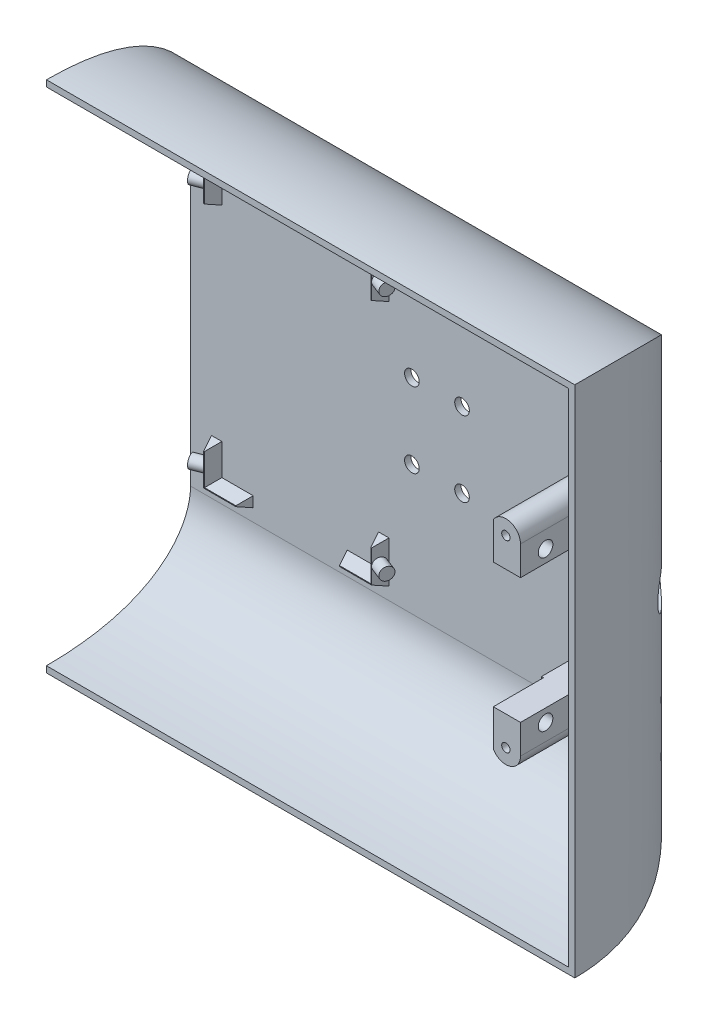
SolidWorks part; units mm, degrees
ref_plane "Plan de face" through (0, 0, 0) normal (0, 0, 1) x (1, 0, 0)
ref_plane "Plan de dessus" through (0, 0, 0) normal (0, 1, 0) x (1, 0, 0)
ref_plane "Plan de droite" through (0, 0, 0) normal (1, 0, 0) x (0, 0, -1)
sketch "Esquisse1" plane through (0, 0, 0) normal (0, 0, 1) x (1, 0, 0)
  line L1 (100.6491, 73.8649) -> (-4.3509, 73.8649)
  line L2 (100.6491, 73.8649) -> (100.6491, -6.1351)
  line L3 (100.6491, -6.1351) -> (-4.3509, -6.1351)
  line L4 (-4.3509, 73.8649) -> (-4.3509, 33.8649)
  line L7 (-4.3509, 33.8649) -> (-4.3509, -6.1351)
  dimension "D1" = 105
  dimension "D2" = 80
extrude "Boss.-Extru.1" add sketch "Esquisse1" along normal blind 1.5
ref_plane "Plan2" through (-4.3509, 0, 0) normal (1, 0, 0) x (0, 0, -1)
sketch "Esquisse3" plane through (0, 0, 1.5) normal (0, 0, 1) x (1, 0, 0)
  line L0 (100.6491, 33.8649) -> (-4.3509, 33.8649) construction
  line L1 (100.6491, -6.1351) -> (100.6491, 73.8649) construction
  line L2 (60.6491, 66.3622) -> (60.6491, 22.1054) construction
  line L3 (48.6491, 66.3622) -> (48.6491, 22.1054) construction
  line L4 (-4.3509, 73.8649) -> (-4.3509, -6.1351) construction
  circle A1 centre (48.6491, 42.8649) radius 1.75
  circle A2 centre (48.6491, 24.8649) radius 1.75
  circle A3 centre (60.6491, 24.8649) radius 1.75
  circle A4 centre (60.6491, 42.8649) radius 1.75
  dimension "D1" = 3.5
  dimension "D2" = 3.5
  dimension "D3" = 3.5
  dimension "D4" = 3.5
  dimension "D7" = 9
  dimension "D8" = 9
  dimension "D9" = 9
  dimension "D5" = 12
  dimension "D6" = 9
  dimension "D10" = 40
extrude "Enlèv. mat.-Extru.1" cut sketch "Esquisse3" against normal up to next
sketch "Esquisse19" plane through (0, 0, 0) normal (0, 0, -1) x (-1, 0, 0)
  line L0 (4.3509, -6.1351) -> (-100.6491, -6.1351)
  line L1 (-100.6491, -6.1351) -> (-100.6491, 73.8649)
  line L2 (-100.6491, 73.8649) -> (4.3509, 73.8649)
sketch "Esquisse4" plane through (0, 0, 1.5) normal (0, 0, -1) x (-1, 0, 0)
  line L0 (-100.6491, 33.8649) -> (-3.0389, 33.8649) construction
  line L1 (-3.1491, -0.6351) -> (-40.6491, -0.6351) construction
  line L2 (-3.1491, -0.6351) -> (-3.1491, 65.8649) construction
  line L3 (-5.6491, 68.3649) -> (-38.1491, 68.3649) construction
  line L4 (-3.1491, 65.8649) -> (-3.1491, 55.8649)
  line L5 (-100.6491, -6.1351) -> (-100.6491, 73.8649) construction
  line L6 (-3.1491, 55.8649) -> (-0.6491, 55.8649)
  line L7 (-0.6491, -3.1351) -> (-43.1491, -3.1351) construction
  line L8 (-0.6491, -3.1351) -> (-0.6491, 65.8649) construction
  line L9 (-5.6491, 70.8649) -> (-38.1491, 70.8649) construction
  line L10 (-43.1491, -3.1351) -> (-43.1491, 65.8649) construction
  line L11 (-40.6491, -0.6351) -> (-40.6491, 65.8649) construction
  line L12 (-0.6491, 55.8649) -> (-0.6491, 65.8649)
  line L13 (-0.6491, 65.8649) -> (-3.1491, 65.8649)
  line L14 (-5.6491, 70.8649) -> (-5.6491, 68.3649)
  line L15 (-40.6491, 65.8649) -> (-40.6491, 55.8649)
  line L16 (-40.6491, 55.8649) -> (-43.1491, 55.8649)
  line L17 (-43.1491, 65.8649) -> (-40.6491, 65.8649)
  line L18 (-38.1491, 70.8649) -> (-38.1491, 68.3649)
  line L19 (-43.1491, 55.8649) -> (-43.1491, 65.8649)
  line L20 (-40.6491, 6.8649) -> (-43.1491, 6.8649)
  line L21 (-43.1491, 6.8649) -> (-43.1491, -3.1351)
  line L22 (-43.1491, -3.1351) -> (-33.1491, -3.1351)
  line L23 (-33.1491, -3.1351) -> (-33.1491, -0.6351)
  line L24 (-33.1491, -0.6351) -> (-40.6491, -0.6351)
  line L25 (-10.6491, -0.6351) -> (-10.6491, -3.1351)
  line L26 (-10.6491, -3.1351) -> (-0.6491, -3.1351)
  line L27 (-0.6491, -3.1351) -> (-0.6491, 6.8649)
  line L28 (-0.6491, 6.8649) -> (-3.1491, 6.8649)
  line L29 (-3.1491, 6.8649) -> (-3.1491, -0.6351)
  line L30 (-3.1491, -0.6351) -> (-10.6491, -0.6351)
  line L31 (-5.6491, 70.8649) -> (-15.6491, 70.8649)
  line L32 (-15.6491, 70.8649) -> (-15.6491, 68.3649)
  line L33 (-15.6491, 68.3649) -> (-5.6491, 68.3649)
  line L34 (-38.1491, 70.8649) -> (-28.1491, 70.8649)
  line L35 (-28.1491, 70.8649) -> (-28.1491, 68.3649)
  line L36 (-28.1491, 68.3649) -> (-38.1491, 68.3649)
  line L37 (-40.6491, 6.8649) -> (-40.6491, -0.6351)
  circle A0 centre (-48.6491, 24.8649) radius 1.75 construction
  point P3 (-70.3996, 0.9688)
  point P4 (-51.6001, 33.8649)
  point P14 (-70.3501, 69.9688)
  dimension "D2" = 2.5
  dimension "D3" = 2.5
  dimension "D4" = 2.5
  dimension "D5" = 34.5
  dimension "D6" = 5.5
  dimension "D7" = 2.5
  dimension "D8" = 32.5
  dimension "D9" = 2.5
  dimension "D10" = 2.5
  dimension "D11" = 34.5
  dimension "D12" = 2.5
  dimension "D13" = 2.5
  dimension "D14" = 10
  dimension "D15" = 10
  dimension "D16" = 10
  dimension "D17" = 10
  dimension "D18" = 10
  dimension "D19" = 10
  dimension "D20" = 10
  dimension "D21" = 10
extrude "Boss.-Extru.2" add sketch "Esquisse4" against normal blind 3 draft 21
sketch "Esquisse7" plane through (-4.3509, 0, 0) normal (-1, 0, 0) x (0, 0, 1)
  line L6 (1.5, 73.8649) -> (0, 73.8649)
  line L7 (36, 95.3649) -> (36, 93.8649)
  line L8 (37.4577, 93.8649) -> (34.5423, 93.8649) construction
  line L10 (1.5, 73.8649) -> (1.5, -6.1351) construction
  line L11 (1.5, 81.9984) -> (1.5, 65.5079) construction
  line L12 (0, 73.8649) -> (0, -6.1351) construction
  line L13 (0, 79.8432) -> (0, 67.8865) construction
  line L14 (59.3831, 95.3649) -> (12.6169, 95.3649) construction
  spline S0 degree 3 poles (0, 73.8649) (0, 82.2935) (9.1969, 95.3649) (36, 95.3649) knots 0 0 0 0 1 1 1 1
  spline S1 degree 3 poles (1.5, 73.8649) (1.5, 82.116) (9.4276, 93.8649) (36, 93.8649) knots 0 0 0 0 1 1 1 1
  dimension "D2" = 36
  dimension "D1" = 20
sweep "Balayage1" add profiles "Esquisse7" path "Esquisse19"
sketch "Esquisse8" plane through (0, 0, 0) normal (0, 0, -1) x (-1, 0, 0)
  line L0 (-100.6491, 33.8649) -> (-183.7283, 33.8649) construction
  line L2 (-105.6491, 64.6793) -> (-105.6491, 3.4231) construction
  line L3 (-100.6491, 73.8649) -> (-100.6491, -6.1351) construction
  line L4 (-100.6491, -6.1351) -> (-100.6491, 73.8649) construction
  circle A0 centre (-105.6491, 55.8649) radius 1
  circle A1 centre (-105.6491, 11.8649) radius 1
  point P2 (-100.6491, 33.8649)
  dimension "D3" = 2
  dimension "D4" = 2
  dimension "D1" = 22
  dimension "D2" = 22
  dimension "D5" = 5
extrude "Enlèv. mat.-Extru.2" cut sketch "Esquisse8" against normal up to next
sketch "Esquisse9" plane through (0, 0, 36) normal (0, 0, 1) x (1, 0, 0)
  line L2 (102.1491, 55.8649) -> (102.1491, 48.8649)
  line L3 (102.1491, 48.8649) -> (109.1491, 48.8649)
  line L4 (109.1491, 55.8649) -> (109.1491, 48.8649)
  line L6 (109.1491, 11.8649) -> (109.1491, 18.8649)
  line L7 (109.1491, 18.8649) -> (102.1491, 18.8649)
  line L8 (102.1491, 11.8649) -> (102.1491, 18.8649)
  circle A0 centre (105.6491, 55.8649) radius 1
  circle A1 centre (105.6491, 11.8649) radius 1
  arc A2 (102.1491, 11.8649) -> (109.1491, 11.8649) centre (105.6491, 11.8649) ccw
  arc A3 (109.1491, 55.8649) -> (102.1491, 55.8649) centre (105.6491, 55.8649) ccw
  dimension "D1" = 2.5
  dimension "D2" = 2.5
  dimension "D3" = 2
  dimension "D4" = 2
  dimension "D5" = 30
extrude "Boss.-Extru.3" add sketch "Esquisse9" against normal up to next
sketch "Esquisse10" plane through (0, 0, 36) normal (0, 0, 1) x (1, 0, 0)
  line L0 (102.6491, 10.0621) -> (102.6491, 18.8649)
  line L2 (102.6491, 48.8649) -> (102.6491, 57.6676)
  line L3 (102.1491, 48.8649) -> (109.1491, 48.8649) construction
  line L4 (102.1491, 55.8649) -> (102.1491, 48.8649) construction
  line L5 (102.1491, 55.8649) -> (102.1491, 48.8649)
  line L6 (102.6491, 48.8649) -> (102.1491, 48.8649)
  line L7 (109.1491, 18.8649) -> (102.1491, 18.8649) construction
  line L8 (102.1491, 18.8649) -> (102.1491, 11.8649) construction
  line L9 (102.6491, 18.8649) -> (102.1491, 18.8649)
  line L10 (102.1491, 18.8649) -> (102.1491, 11.8649)
  line L11 (100.6491, 73.8649) -> (100.6491, -6.1351) construction
  circle A0 centre (105.6491, 55.8649) radius 3.5 construction
  circle A1 centre (105.6491, 11.8649) radius 3.5 construction
  arc A2 (109.1491, 55.8649) -> (102.1491, 55.8649) centre (105.6491, 55.8649) ccw construction
  arc A3 (102.1491, 11.8649) -> (109.1491, 11.8649) centre (105.6491, 11.8649) ccw construction
  arc A4 (102.6491, 57.6676) -> (102.1491, 55.8649) centre (105.6491, 55.8649) ccw
  arc A5 (102.1491, 11.8649) -> (102.6491, 10.0621) centre (105.6491, 11.8649) ccw
  dimension "D1" = 2
extrude "Enlèv. mat.-Extru.3" cut sketch "Esquisse10" against normal blind 12
sketch "Esquisse11" plane through (102.6491, 0, 0) normal (-1, 0, 0) x (0, 0, 1)
  line L0 (30, 48.8649) -> (30, 18.8649) construction
  line L4 (24, 48.8649) -> (36, 48.8649) construction
  line L5 (24, 18.8649) -> (36, 18.8649) construction
  line L6 (30, 48.8649) -> (30, 51.8649) construction
  line L7 (30, 15.8649) -> (30, 18.8649) construction
  circle A0 centre (30, 51.8649) radius 1.75
  circle A1 centre (30, 15.8649) radius 1.75
  point P6 (30, 48.8649)
  point P7 (30, 18.8649)
  dimension "D1" = 3.5
  dimension "D2" = 3.5
  dimension "D3" = 36
extrude "Enlèv. mat.-Extru.4" cut sketch "Esquisse11" against normal up to next
sketch "Esquisse16" plane through (102.1491, 0, 0) normal (-1, 0, 0) x (0, 0, 1)
  line L0 (1.5857, 48.8649) -> (1.5857, 55.8649) construction
  line L1 (1.5857, 39.8649) -> (16.5857, 39.8649)
  line L2 (1.5857, 39.8649) -> (1.5857, 27.8649)
  line L3 (1.5857, 27.8649) -> (16.5857, 27.8649)
  line L4 (16.5857, 39.8649) -> (16.5857, 27.8649)
  line L6 (1.5857, 48.8649) -> (24, 48.8649) construction
  line L7 (1.5857, 18.8649) -> (24, 18.8649) construction
  line L8 (16.5857, 39.8649) -> (16.5857, 48.8649) construction
  line L9 (16.5857, 27.8649) -> (16.5857, 18.8649) construction
  dimension "D1" = 15
  dimension "D2" = 12
extrude "Boss.-Extru.4" add sketch "Esquisse16" against normal up to next
sketch "Esquisse12" plane through (157.424, 0, -57.2977) normal (0.9397, 0, -0.342) x (-0.342, 0, -0.9397)
  circle A0 centre (-44.7183, 33.8649) radius 4.25
  dimension "D1" = 8.5
extrude "Enlèv. mat.-Extru.5" cut sketch "Esquisse12" against normal up to surface (73.5516 mm away)
sketch "Esquisse17" plane through (0, 0, 16.5857) normal (0, 0, 1) x (1, 0, 0)
  line L0 (117.8029, 39.8649) -> (102.1491, 39.8649) construction
  line L1 (107.1491, 39.8649) -> (111.1491, 39.8649)
  line L2 (107.1491, 39.8649) -> (107.1491, 27.8649)
  line L3 (107.1491, 27.8649) -> (111.1491, 27.8649)
  line L4 (111.1491, 39.8649) -> (111.1491, 27.8649)
  line L5 (117.8029, 27.8649) -> (102.1491, 27.8649) construction
  line L6 (102.1491, 27.8649) -> (102.1491, 39.8649) construction
  point P8 (102.1491, 33.8649)
  dimension "D1" = 4
  dimension "D2" = 5
extrude "Enlèv. mat.-Extru.6" cut sketch "Esquisse17" against normal blind 8
sketch "Esquisse20" plane through (0.0639, 0, -0.0245) normal (-0.9336, 0, 0.3584) x (0.3584, 0, 0.9336)
  line L0 (4.8464, 57.0165) -> (4.8464, 64.7133) construction
  line L1 (4.8464, 60.8649) -> (2.5987, 60.8649) construction
  line L2 (4.8464, -1.9835) -> (4.8464, 5.7133) construction
  line L3 (4.8464, 1.8649) -> (4.8918, 1.8649) construction
  circle A0 centre (3.3464, 60.8649) radius 1.5
  circle A1 centre (3.3464, 1.8649) radius 1.5
  point P4 (4.8464, 60.8649)
  point P9 (4.8464, 1.8649)
  dimension "D1" = 3
  dimension "D2" = 3
extrude "Boss.-Extru.5" add sketch "Esquisse20" along normal blind 3
sketch "Esquisse21" plane through (38.1094, 0, 14.6288) normal (0.9336, 0, 0.3584) x (0.3584, 0, -0.9336)
  line L0 (10.8494, 64.7133) -> (10.8494, 57.0165) construction
  line L1 (10.8494, 5.7133) -> (10.8494, -1.9835) construction
  line L2 (10.8494, 1.8649) -> (-0.6031, 1.8649) construction
  line L3 (10.8494, 60.8649) -> (-0.9717, 60.8649) construction
  circle A0 centre (12.3494, 60.8649) radius 1.5
  circle A1 centre (12.3494, 1.8649) radius 1.5
  point P4 (10.8494, 60.8649)
  point P5 (10.8494, 1.8649)
  dimension "D1" = 3
  dimension "D2" = 3
extrude "Boss.-Extru.6" add sketch "Esquisse21" along normal blind 3
